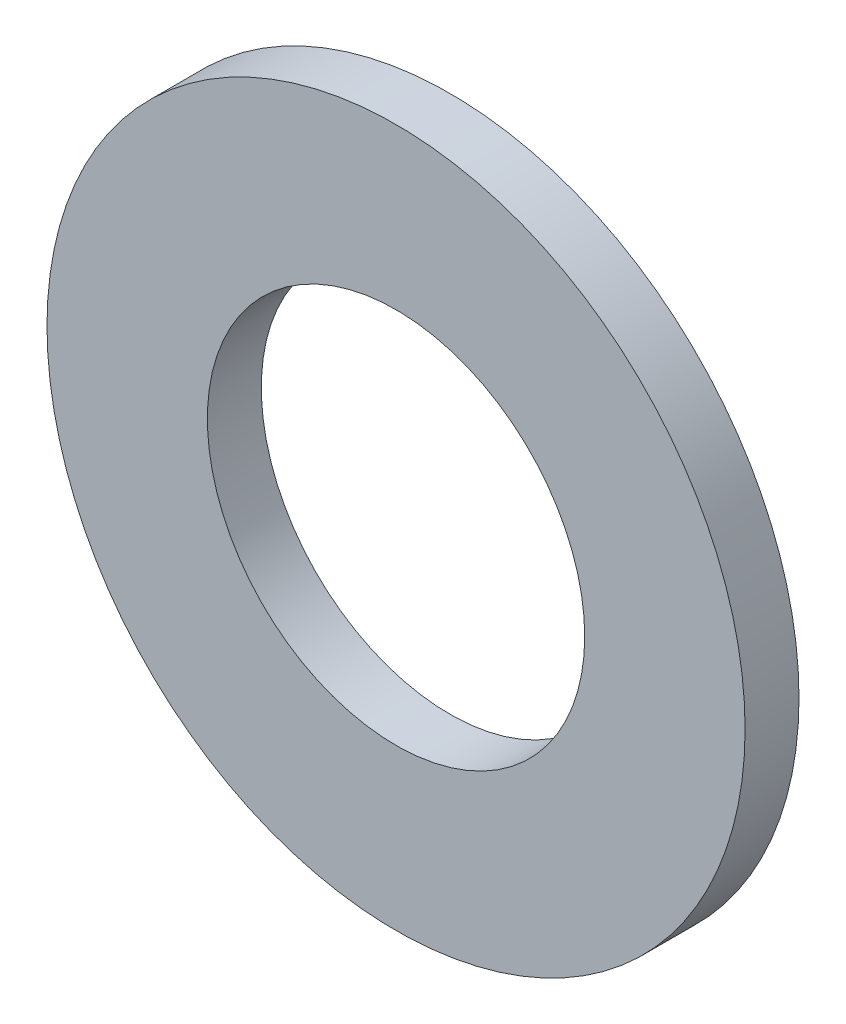
SolidWorks part; units mm, degrees
material "Copper"
ref_plane "Front Plane" through (0, 0, 0) normal (0, 0, 1) x (1, 0, 0)
ref_plane "Top Plane" through (0, 0, 0) normal (0, 1, 0) x (1, 0, 0)
ref_plane "Right Plane" through (0, 0, 0) normal (1, 0, 0) x (0, 0, -1)
sketch "Sketch1" plane through (0, 0, 0) normal (0, 0, 1) x (1, 0, 0)
  circle A0 centre (0, 0) radius 12.95
  circle A1 centre (0, 0) radius 7
  dimension "D1" = 25.9
  dimension "D2" = 14
extrude "Boss-Extrude1" add sketch "Sketch1" along normal blind 2
